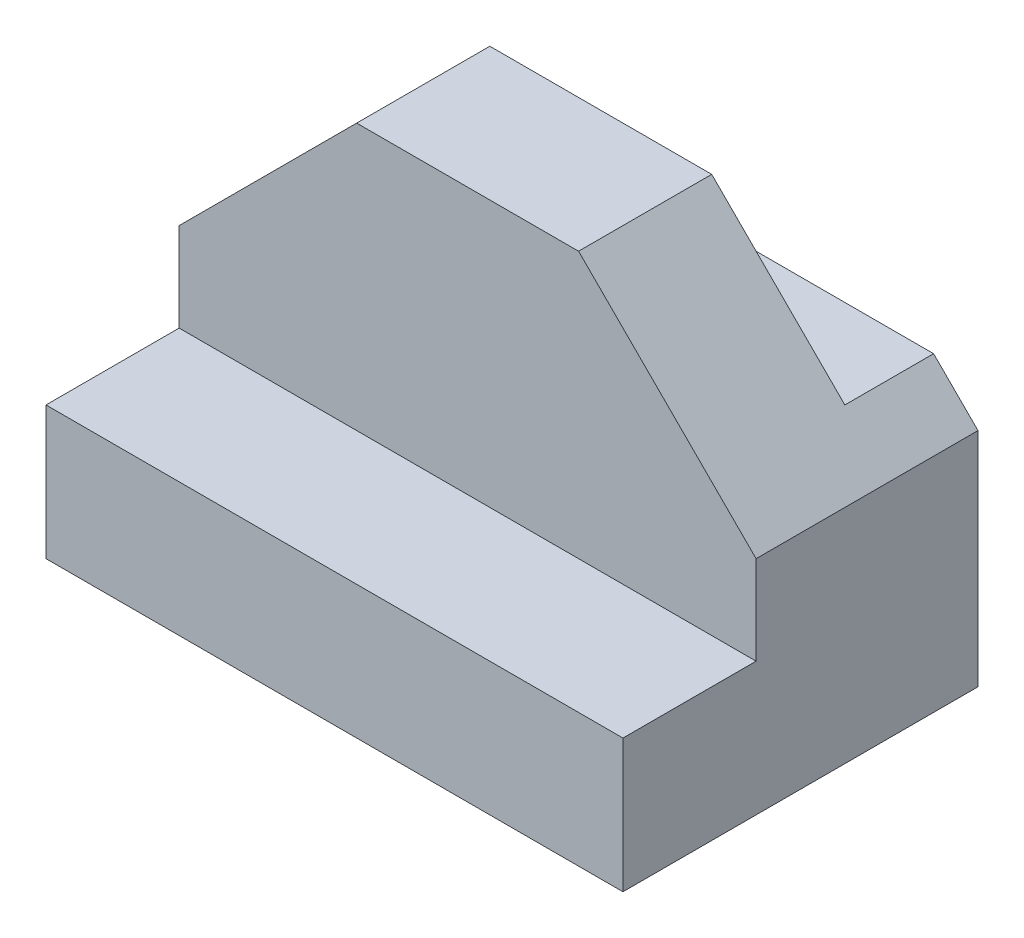
SolidWorks part; units mm, degrees
ref_plane "Plan de face" through (0, 0, 0) normal (0, 0, 1) x (1, 0, 0)
ref_plane "Plan de dessus" through (0, 0, 0) normal (0, 1, 0) x (1, 0, 0)
ref_plane "Plan de droite" through (0, 0, 0) normal (1, 0, 0) x (0, 0, -1)
sketch "Esquisse1" plane through (0, 0, 0) normal (1, 0, 0) x (0, 0, -1)
  line L0 (-20.6942, -12.6335) -> (19.3058, -12.6335)
  line L1 (19.3058, -12.6335) -> (19.3058, 17.3665)
  line L2 (19.3058, 17.3665) -> (9.3058, 17.3665)
  line L3 (9.3058, 17.3665) -> (9.3058, 32.3665)
  line L4 (9.3058, 32.3665) -> (-5.6942, 32.3665)
  line L5 (-5.6942, 32.3665) -> (-5.6942, 2.3665)
  line L6 (-5.6942, 2.3665) -> (-20.6942, 2.3665)
  line L7 (-20.6942, 2.3665) -> (-20.6942, -12.6335)
  dimension "D1" = 40
  dimension "D2" = 15
  dimension "D3" = 15
  dimension "D4" = 30
  dimension "D5" = 30
  dimension "D6" = 10
  dimension "D7" = 15
  dimension "15" = 15
extrude "Boss.-Extru.1" add sketch "Esquisse1" along normal blind 65
chamfer "Chanfrein4" distance 20 angle 45 1 edges at (65, 32.3665, -1.8058)
chamfer "Chanfrein5" distance 20 angle 45 1 edges at (0, 32.3665, -1.8058)
